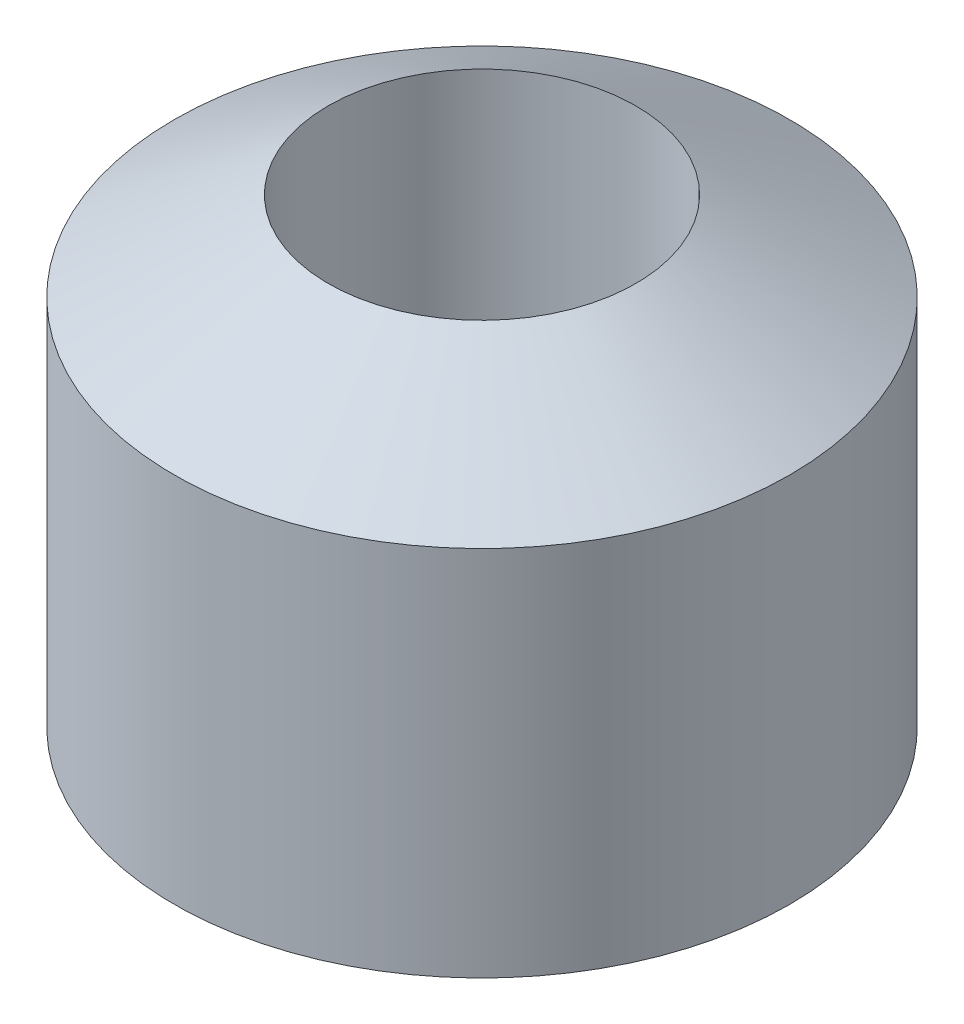
SolidWorks part; units mm, degrees
ref_plane "Front Plane" through (0, 0, 0) normal (0, 0, 1) x (1, 0, 0)
ref_plane "Top Plane" through (0, 0, 0) normal (0, 1, 0) x (1, 0, 0)
ref_plane "Right Plane" through (0, 0, 0) normal (1, 0, 0) x (0, 0, -1)
sketch "Sketch1" plane through (0, 0, 0) normal (0, 0, 1) x (1, 0, 0)
  line L0 (0, 3.9802) -> (0, -100792.4922) construction
  line L1 (0, 0) -> (100796.4725, 0) construction
  line L2 (14, 50) -> (14, 0)
  line L3 (14, 0) -> (28, 8.0829)
  line L4 (28, 8.0829) -> (28, 41.9171)
  line L5 (28, 41.9171) -> (14, 50)
  dimension "D1" = 50
  dimension "D2" = 60
  dimension "D3" = 60
  dimension "D4" = 28
  dimension "D5" = 56
revolve "Revolve1" add sketch "Sketch1" angle 360 about L0
